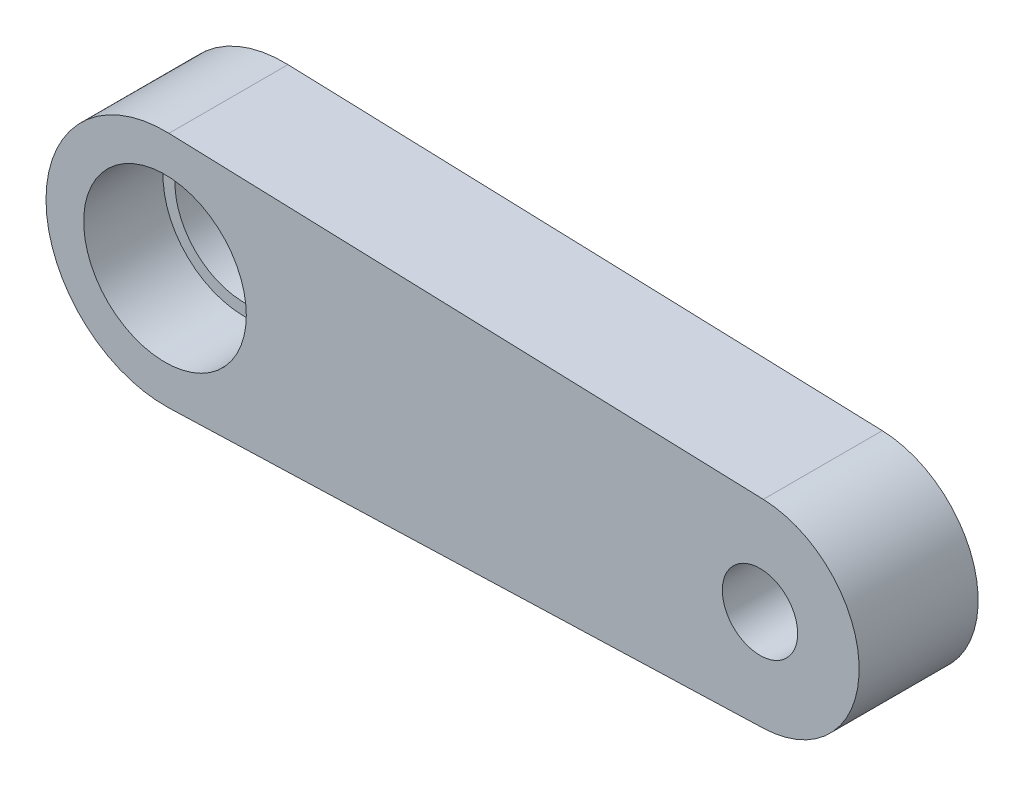
SolidWorks part; units mm, degrees
ref_plane "正面" through (0, 0, 0) normal (0, 0, 1) x (1, 0, 0)
ref_plane "平面" through (0, 0, 0) normal (0, 1, 0) x (1, 0, 0)
ref_plane "右側面" through (0, 0, 0) normal (1, 0, 0) x (0, 0, -1)
sketch "ｽｹｯﾁ1" plane through (0, 0, 0) normal (0, 0, 1) x (1, 0, 0)
  line L0 (0.1667, 4.9972) -> (-29.8, 5.9967)
  line L1 (0.1667, -4.9972) -> (-29.8, -5.9967)
  arc A0 (0.1667, 4.9972) -> (0.1667, -4.9972) centre (0, 0) cw
  arc A1 (-29.8, 5.9967) -> (-29.8, -5.9967) centre (-30, 0) ccw
  dimension "D1" = 5
  dimension "D2" = 6
  dimension "D3" = 30
extrude "ﾎﾞｽ - 押し出し1" add sketch "ｽｹｯﾁ1" along normal blind 6
sketch "ｽｹｯﾁ3" plane through (0, 0, 0) normal (0, 0, -1) x (-1, 0, 0)
  circle A0 centre (0, 0) radius 4.1
  dimension "D1" = 8.2
extrude "ｶｯﾄ - 押し出し2" cut sketch "ｽｹｯﾁ3" against normal blind 1.2 contours A0
sketch "ｽｹｯﾁ4" plane through (0, 0, 6) normal (0, 0, 1) x (1, 0, 0)
  circle A0 centre (-30, 0) radius 4.1
  arc A1 (-29.8, 5.9967) -> (-29.8, -5.9967) centre (-30, 0) ccw construction
  dimension "D1" = 8.2
extrude "ｶｯﾄ - 押し出し3" cut sketch "ｽｹｯﾁ4" against normal blind 4
sketch "ｽｹｯﾁ5" plane through (0, 0, 6) normal (0, 0, 1) x (1, 0, 0)
  circle A0 centre (-30, 0) radius 3.5
  dimension "D1" = 7
extrude "ｶｯﾄ - 押し出し5" cut sketch "ｽｹｯﾁ5" against normal through all
sketch "ｽｹｯﾁ6" plane through (0, 0, 6) normal (0, 0, 1) x (1, 0, 0)
  circle A0 centre (0, 0) radius 1.9
  dimension "D1" = 3.8
extrude "ｶｯﾄ - 押し出し6" cut sketch "ｽｹｯﾁ6" against normal through all both and the other way through all
